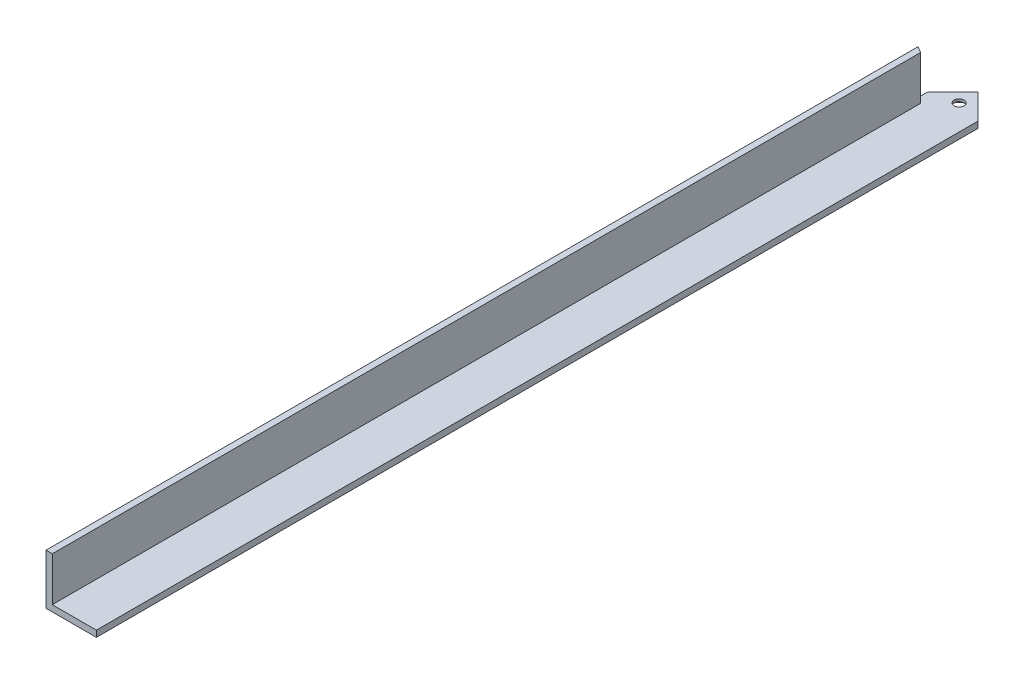
SolidWorks part; units mm, degrees
material "6061 Alloy"
ref_plane "Front Plane" through (0, 0, 0) normal (0, 0, 1) x (1, 0, 0)
ref_plane "Top Plane" through (0, 0, 0) normal (0, 1, 0) x (1, 0, 0)
ref_plane "Right Plane" through (0, 0, 0) normal (1, 0, 0) x (0, 0, -1)
sketch "Sketch1" plane through (0, 0, 0) normal (0, 0, 1) x (1, 0, 0)
  line L0 (0, 50.8) -> (0, 0)
  line L1 (0, 0) -> (50.8, 0)
  line L2 (50.8, 0) -> (50.8, 6.35)
  line L3 (50.8, 6.35) -> (6.35, 6.35)
  line L4 (6.35, 6.35) -> (6.35, 50.8)
  line L5 (6.35, 50.8) -> (0, 50.8)
  dimension "D1" = 6.35
  dimension "D2" = 50.8
extrude "Boss-Extrude1" add sketch "Sketch1" along normal blind 914.4
sketch "Sketch2" plane through (0, 6.35, 0) normal (0, 1, 0) x (1, 0, 0)
  line L1 (0, 0) -> (50.8, 0) construction
  circle A0 centre (25.4, 0) radius 43.18
  dimension "D1" = 86.36
extrude "Cut-Extrude1" cut sketch "Sketch2" along normal up to next
sketch "Sketch3" plane through (0, 6.35, 0) normal (0, 1, 0) x (1, 0, 0)
  line L1 (50.8, 0) -> (0, 0) construction
  line L4 (25.4, 0) -> (-1.5408, -26.9408)
  line L5 (25.4, 0) -> (52.3408, -26.9408)
  arc A0 (52.3408, -26.9408) -> (-1.5408, -26.9408) centre (25.4, 0) ccw
  dimension "D1" = 45
  dimension "D2" = 76.2
  dimension "D3" = 45
extrude "Cut-Extrude2" cut sketch "Sketch3" against normal blind 1219.2
hole_wizard "CSK for 3/8 Flat Head Machine Screw (100)1" positions "Sketch7" profile "Sketch6" countersink size "3/8" standard "ANSI Inch" end condition through all
sketch "Sketch7" plane through (0, 0, 0) normal (0, -1, 0) x (-1, 0, 0)
  line L0 (-25.4, 0) -> (-25.4, -19.05) construction
  point P0 (-25.4, -19.05)
  dimension "D1" = 19.05
sketch "Sketch6" plane through (25.4, 0, 19.05) normal (1, 0, 0) x (0, 0, -1)
  line L0 (0, 0) -> (0, 50.8)
  line L1 (0, 50.8) -> (5.0419, 50.8)
  line L2 (5.0419, 50.8) -> (5.0419, 3.8896)
  line L3 (5.0419, 3.8896) -> (9.6774, 0)
  line L5 (9.6774, 0) -> (0, 0)
  line L6 (-5.0419, 3.8896) -> (-9.6774, 0) construction
  line L11 (0, -6.35) -> (0, 107.95) construction
  dimension "Thru Hole Dia." = 10.0838
  dimension "Thru Hole Depth" = 50.8
  dimension "Near C'Sink Dia." = 19.3548
  dimension "Near C'Sink Angle" = 100
